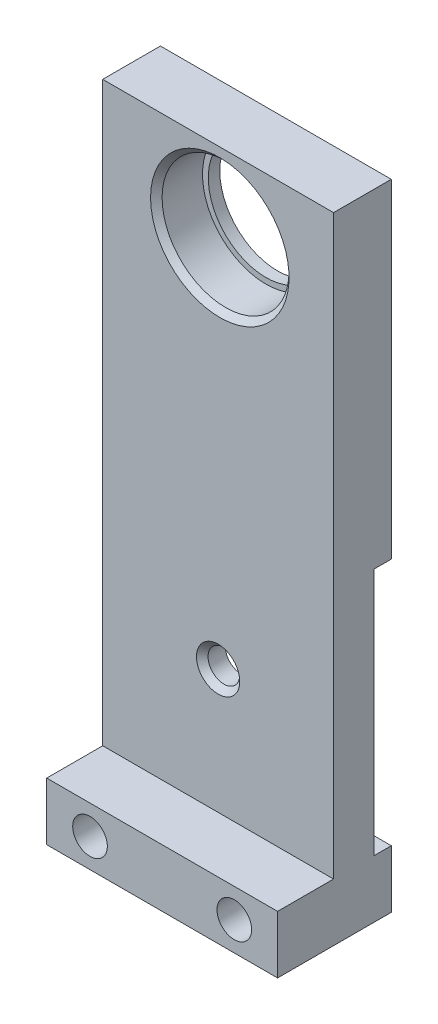
SolidWorks part; units mm, degrees
ref_plane "Ebene vorne" through (0, 0, 0) normal (0, 0, 1) x (1, 0, 0)
ref_plane "Ebene oben" through (0, 0, 0) normal (0, 1, 0) x (1, 0, 0)
ref_plane "Ebene rechts" through (0, 0, 0) normal (1, 0, 0) x (0, 0, -1)
sketch "Skizze1" plane through (0, 0, 0) normal (0, 0, 1) x (1, 0, 0)
  line L1 (0, 0) -> (40, 0)
  line L2 (0, 0) -> (0, 110)
  line L3 (0, 110) -> (40, 110)
  line L4 (40, 0) -> (40, 110)
  dimension "D1" = 40
  dimension "D2" = 110
extrude "Aufsatz-Linear austragen1" add sketch "Skizze1" along normal blind 10
sketch "Skizze2" plane through (0, 0, 0) normal (0, 0, -1) x (-1, 0, 0)
  line L0 (-40, 0) -> (-40, 110) construction
  line L1 (-40, 10) -> (0, 10)
  line L2 (-40, 10) -> (-40, 53)
  line L3 (-40, 53) -> (0, 53)
  line L4 (0, 10) -> (0, 53)
  line L5 (0, 110) -> (0, 0) construction
  line L6 (0, 0) -> (-40, 0) construction
  dimension "D1" = 10
  dimension "D2" = 43
extrude "Schnitt-Linear austragen1" cut sketch "Skizze2" against normal blind 3
sketch "Skizze3" plane through (0, 0, 3) normal (0, 0, -1) x (-1, 0, 0)
  line L0 (-40, 53) -> (-40, 10) construction
  line L1 (-40, 10) -> (0, 10) construction
  circle A0 centre (-20, 31.5) radius 2.75
  dimension "D3" = 5.5
  dimension "D1" = 20
  dimension "D2" = 21.5
extrude "Schnitt-Linear austragen2" cut sketch "Skizze3" against normal blind 11
sketch "Skizze4" plane through (0, 0, 0) normal (0, 0, -1) x (-1, 0, 0)
  circle A0 centre (-20.2905, 96.4) radius 11
  circle A1 centre (-20, 31.5) radius 2.75 construction
  dimension "D1" = 22
  dimension "D2" = 64.9
sketch "Skizze5" plane through (0, 0, 10) normal (0, 0, 1) x (1, 0, 0)
  circle A0 centre (20.2905, 96.4) radius 11
extrude "Schnitt-Linear austragen4" cut sketch "Skizze5" against normal blind 8
sketch "Skizze6" plane through (0, 0, 2) normal (0, 0, 1) x (1, 0, 0)
  circle A0 centre (20.2905, 96.4) radius 10
extrude "Schnitt-Linear austragen5" cut sketch "Skizze6" against normal blind 8
chamfer "Fase1" distance 1 angle 45 2 edges at (17.25, 31.5, 10) (31.2905, 96.4, 10)
sketch "Skizze7" plane through (0, 0, 10) normal (0, 0, 1) x (1, 0, 0)
  circle A0 centre (20, 31.5) radius 14.681
  dimension "D1" = 29.362
sketch "Skizze8" plane through (0, 0, 10) normal (0, 0, 1) x (1, 0, 0)
  circle A0 centre (20.2905, 96.4) radius 53.1
  dimension "D1" = 106.2
sketch "Skizze10" plane through (0, 0, 10) normal (0, 0, 1) x (1, 0, 0)
  line L0 (40, 0) -> (40, 110) construction
  line L1 (0, 0) -> (40, 0)
  line L2 (0, 0) -> (0, 10)
  line L3 (0, 10) -> (40, 10)
  line L4 (40, 0) -> (40, 10)
  dimension "D1" = 10
extrude "Aufsatz-Linear austragen2" add sketch "Skizze10" along normal blind 9.7
sketch "Skizze11" plane through (0, 0, 0) normal (0, 0, -1) x (-1, 0, 0)
  line L0 (-40, 10) -> (0, 10) construction
  line L1 (-40, 10) -> (0, 10) construction
  line L2 (0, 10) -> (0, 0) construction
  line L3 (-40, 0) -> (-40, 10) construction
  circle A0 centre (-32.5, 5) radius 3
  circle A1 centre (-7.5, 5) radius 3
  dimension "D1" = 6
  dimension "D2" = 6
  dimension "D3" = 5
  dimension "D4" = 5
  dimension "D5" = 7.5
  dimension "D6" = 7.5
extrude "Schnitt-Linear austragen6" cut sketch "Skizze11" against normal blind 21
sketch "Skizze12" plane through (0, 0, 0) normal (0, 0, -1) x (-1, 0, 0)
  circle A0 centre (-32.5, 5) radius 4.5
  circle A1 centre (-7.5, 5) radius 4.5
  dimension "D1" = 9
  dimension "D2" = 9
extrude "Schnitt-Linear austragen7" cut sketch "Skizze12" against normal blind 13
sketch "Skizze13" plane through (0, 0, 3) normal (0, 0, -1) x (-1, 0, 0)
  circle A0 centre (-20, 31.5) radius 11.25
  dimension "D1" = 22.5
extrude "Schnitt-Linear austragen8" cut sketch "Skizze13" against normal blind 3
